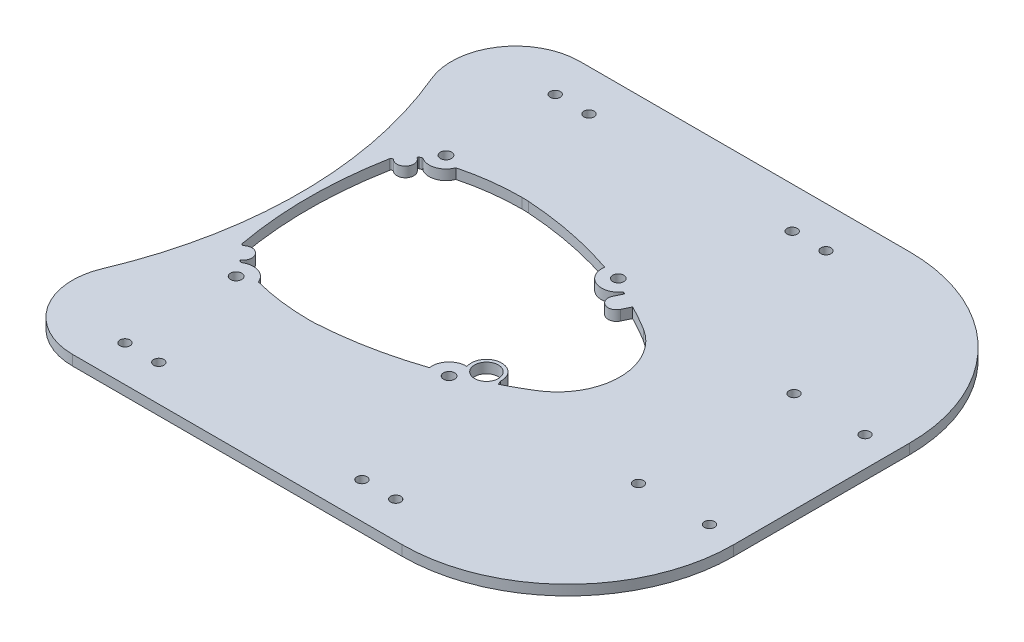
SolidWorks part; units mm, degrees
ref_plane "前视基准面" through (0, 0, 0) normal (0, 0, 1) x (1, 0, 0)
ref_plane "上视基准面" through (0, 0, 0) normal (0, 1, 0) x (1, 0, 0)
ref_plane "右视基准面" through (0, 0, 0) normal (1, 0, 0) x (0, 0, -1)
sketch "草图1" plane through (0, 0, 0) normal (0, 1, 0) x (1, 0, 0)
  line L1 (-102.5, -75) -> (102.5, -75)
  line L2 (-102.5, -75) -> (-102.5, 75)
  line L3 (-102.5, 75) -> (102.5, 75)
  line L4 (102.5, -75) -> (102.5, 75)
  line L5 (-102.5, -75) -> (102.5, 75) construction
  line L6 (-102.5, 75) -> (102.5, -75) construction
  point P0 (0, 0)
  dimension "D1" = 150
  dimension "D2" = 205
extrude "凸台-拉伸1" add sketch "草图1" along normal blind 3
fillet "圆角4" radius 49 4 edges at (102.5, 1.5, 75) (102.5, 1.5, -75) (-102.5, 1.5, -75) (-102.5, 1.5, 75)
sketch "草图7" plane through (0, 3, 0) normal (0, 1, 0) x (1, 0, 0)
  circle A4 centre (-29.1574, -64.3015) radius 1.5
  circle A5 centre (-39.1574, -64.3015) radius 1.5
  circle A6 centre (30.8947, -64.3015) radius 1.5
  circle A7 centre (40.8947, -64.3015) radius 1.5
extrude "切除-拉伸8" cut sketch "草图7" against normal blind 3
sketch "草图9" plane through (0, 3, 0) normal (0, 1, 0) x (1, 0, 0)
  circle A4 centre (-39.1574, 62.8977) radius 1.5
  circle A5 centre (-29.1574, 62.8977) radius 1.5
  circle A6 centre (30.8947, 62.8977) radius 1.5
  circle A7 centre (40.8947, 62.8977) radius 1.5
extrude "切除-拉伸10" cut sketch "草图9" against normal blind 10
sketch "草图10" plane through (0, 3, 0) normal (0, 1, 0) x (1, 0, 0)
  line L0 (-73.5433, 70.7131) -> (-101.7166, 64.6417)
  line L1 (-101.7166, 64.6417) -> (-120.7329, 20.0424)
  line L2 (-120.7329, 20.0424) -> (-122.2378, -19.2215)
  line L3 (-122.2378, -19.2215) -> (-120.7329, -55.0652)
  line L4 (-120.7329, -55.0652) -> (-105.1368, -72.987)
  line L5 (-105.1368, -72.987) -> (-73.5433, -70.7131)
  arc A0 (-73.5433, 70.7131) -> (-73.5433, -70.7131) centre (-176.7188, 0) cw
  arc A1 (-53.5, 75) -> (-102.5, 26) centre (-53.5, 26) ccw construction
  arc A2 (-102.5, -26) -> (-53.5, -75) centre (-53.5, -26) ccw construction
extrude "切除-拉伸11" cut sketch "草图10" against normal blind 10
fillet "圆角6" radius 19 2 edges at (-73.5433, 1.5, 70.7131) (-73.5433, 1.5, -70.7131)
sketch "草图12" plane through (0, 0, 0) normal (0, -1, 0) x (1, 0, 0)
  arc A8 (18.8978, 24.8951) -> (15.5979, 24.8762) centre (17.2479, 24.8856) ccw
  arc A9 (15.5979, 24.8762) -> (18.8978, 24.8951) centre (17.2479, 24.8856) ccw
  arc A10 (-38.1065, 30.8538) -> (-41.4064, 30.8349) centre (-39.7565, 30.8444) ccw
  arc A11 (-41.4064, 30.8349) -> (-38.1065, 30.8538) centre (-39.7565, 30.8444) ccw
  arc A12 (-38.0616, -31.1462) -> (-41.3616, -31.1651) centre (-39.7116, -31.1556) ccw
  arc A13 (-41.3616, -31.1651) -> (-38.0616, -31.1462) centre (-39.7116, -31.1556) ccw
  arc A14 (18.934, -25.1049) -> (15.6341, -25.1238) centre (17.284, -25.1144) ccw
  arc A15 (15.6341, -25.1238) -> (18.934, -25.1049) centre (17.284, -25.1144) ccw
extrude "切除-拉伸12" cut sketch "草图12" against normal blind 10
sketch "草图13" plane through (0, 0, 0) normal (0, -1, 0) x (1, 0, 0)
  line L4 (26.6148, 19.6122) -> (26.6662, 19.7183)
  line L5 (26.1598, 18.6664) -> (26.6148, 19.6122)
  line L6 (25.5325, -17.527) -> (26.6904, -19.9357)
  line L7 (22.1857, -22.1056) -> (21.0261, -19.6931)
  line L8 (12.4104, -25.9802) -> (12.3869, -25.836)
  line L9 (-47.1197, 21.6577) -> (-47.2203, 21.6765)
  arc A38 (-15.7291, -31.5759) -> (12.4104, -25.9802) centre (-22.6349, 76.7042) ccw
  arc A39 (-17.7112, -31.6397) -> (-15.7291, -31.5759) centre (-17.734, -0.1397) ccw
  arc A40 (-35.0726, -29.4288) -> (-17.7112, -31.6397) centre (-17.7611, 37.2403) ccw
  arc A41 (-35.0726, -29.4288) -> (-42.3545, -26.9702) centre (-39.7116, -31.1556) ccw
  arc A42 (-42.6229, -26.9963) -> (-42.3545, -26.9702) centre (-42.5147, -26.7166) ccw
  arc A43 (-43.249, -26.7505) -> (-42.6229, -26.9963) centre (-17.7611, 37.2403) ccw
  arc A44 (-43.3072, -26.224) -> (-43.249, -26.7505) centre (-43.138, -26.4718) ccw
  arc A45 (-43.3072, -26.224) -> (-42.2167, -24.1449) centre (-44.7167, -24.1593) ccw
  arc A46 (-42.2167, -24.1449) -> (-46.3672, -22.2816) centre (-44.7167, -24.1593) ccw
  arc A47 (-47.1887, -21.9985) -> (-46.3672, -22.2816) centre (-46.6973, -21.9061) ccw
  arc A48 (-49.2321, -0.7557) -> (-47.1887, -21.9985) centre (69.2659, -0.0768) ccw
  arc A49 (-47.2203, 21.6765) -> (-49.2321, -0.7557) centre (69.2659, -0.0768) ccw
  arc A50 (-44.3688, 21.2245) -> (-43.2648, 26.0273) centre (-44.7514, 23.8407) ccw
  arc A51 (-43.234, 26.3004) -> (-43.2648, 26.0273) centre (-43.1761, 26.1556) ccw
  arc A52 (-42.47, 26.5332) -> (-42.6096, 26.5466) centre (-42.5531, 26.4012) ccw
  arc A53 (-42.6096, 26.5466) -> (-43.234, 26.3004) centre (-17.707, -37.5197) ccw
  arc A54 (-42.47, 26.5332) -> (-35.0066, 29.0036) centre (-39.7565, 30.8444) ccw
  arc A55 (-17.7567, 31.2162) -> (-35.0066, 29.0036) centre (-17.707, -37.5197) ccw
  arc A56 (-15.7836, 31.1555) -> (-17.7567, 31.2162) centre (-17.734, -0.1397) ccw
  arc A57 (12.2111, 25.6472) -> (-15.7836, 31.1555) centre (-22.5237, -76.9906) ccw
  arc A58 (12.2111, 25.6472) -> (17.4425, 19.7953) centre (17.2479, 24.8856) ccw
  arc A59 (25.177, 18.2928) -> (22.4277, 21.6912) centre (21.677, 18.2727) ccw
  arc A60 (22.4277, 21.6912) -> (18.7403, 20.1768) centre (21.677, 18.2727) ccw
  arc A61 (18.7403, 20.1768) -> (18.1771, 18.2527) centre (21.677, 18.2727) ccw
  arc A62 (18.1771, 18.2527) -> (25.177, 18.2928) centre (21.677, 18.2727) ccw
  arc A63 (19.453, 14.3607) -> (19.4759, 14.3478) centre (21.677, 18.2727) ccw
  arc A64 (17.4425, 19.7953) -> (19.453, 14.3607) centre (21.677, 18.2727) ccw
  arc A65 (19.4759, 14.3478) -> (26.177, 18.2985) centre (21.677, 18.2727) ccw
  arc A66 (26.177, 18.2985) -> (26.1598, 18.6664) centre (21.677, 18.2727) ccw
  arc A67 (33.8838, 15.694) -> (26.6662, 19.7183) centre (-22.5237, -76.9906) ccw
  arc A68 (42.7656, -0.0033) -> (33.8838, 15.694) centre (24.2659, -0.1093) ccw
  arc A69 (33.9067, -15.8988) -> (42.7656, -0.0033) centre (24.2659, -0.1093) ccw
  arc A70 (26.6904, -19.9357) -> (33.9067, -15.8988) centre (-22.6349, 76.7042) ccw
  arc A71 (25.5325, -17.527) -> (20.7794, -18.6244) centre (23.2793, -18.61) ccw
  arc A72 (20.7794, -18.6244) -> (21.0261, -19.6931) centre (23.2793, -18.61) ccw
  arc A73 (22.0545, -22.165) -> (22.1857, -22.1056) centre (-22.6349, 76.7042) ccw
  arc A74 (21.4475, -22.4371) -> (22.0545, -22.165) centre (-22.6349, 76.7042) ccw
  arc A75 (21.4475, -22.4371) -> (12.3869, -25.836) centre (17.284, -25.1144) ccw
  spline S5 degree 3 poles (-46.4755, 21.8737) (-46.4814, 21.879) (-46.4937, 21.8893) (-46.5133, 21.9038) (-46.5339, 21.9171) (-46.5553, 21.9291) (-46.5779, 21.9399) (-46.6017, 21.9495) (-46.6272, 21.9578) (-46.6538, 21.9645) (-46.6805, 21.9693) (-46.7093, 21.9724) (-46.7384, 21.9733) (-46.7671, 21.972) (-46.7957, 21.9687) (-46.8243, 21.9632) (-46.853, 21.9554) (-46.8812, 21.9453) (-46.9081, 21.9334) (-46.9338, 21.9196) (-46.9584, 21.9039) (-46.982, 21.8863) (-47.0038, 21.8673) (-47.0245, 21.8464) (-47.0431, 21.8245) (-47.0597, 21.8018) (-47.0742, 21.7787) (-47.0867, 21.7555) (-47.0975, 21.7318) (-47.1066, 21.7076) (-47.1142, 21.6826) (-47.118, 21.666) (-47.1197, 21.6577) knots 0 0 0 0 0.033333 0.066667 0.1 0.133333 0.166667 0.2 0.233333 0.266667 0.3 0.333333 0.366667 0.4 0.433333 0.466667 0.5 0.533333 0.566667 0.6 0.633333 0.666667 0.7 0.733333 0.766667 0.8 0.833333 0.866667 0.9 0.933333 0.966667 1 1 1 1 weights 1 1 1 1 1 1 1 1 1 1 1 1 1 1 1 1 1 1 1 1 1 1 1 1 1 1 1 1 1 1 1 1 1
  spline S6 degree 3 poles (-46.4755, 21.8737) (-46.4415, 21.8443) (-46.3735, 21.7854) (-46.2671, 21.7046) (-46.1576, 21.6292) (-46.0447, 21.5596) (-45.9284, 21.4957) (-45.7752, 21.4209) (-45.5833, 21.3436) (-45.3519, 21.2729) (-45.198, 21.2441) (-45.1198, 21.2295) knots 0 0 0 0 0.081532 0.163516 0.24623 0.329946 0.414924 0.501414 0.663064 0.828812 1 1 1 1
  spline S7 degree 3 poles (-45.1198, 21.2295) (-45.1035, 21.2269) (-45.0702, 21.2219) (-45.0186, 21.2152) (-44.9662, 21.2095) (-44.9129, 21.205) (-44.8587, 21.2015) (-44.8032, 21.1992) (-44.7477, 21.1982) (-44.6921, 21.1984) (-44.6368, 21.1998) (-44.5822, 21.2025) (-44.5282, 21.2063) (-44.4745, 21.2112) (-44.4212, 21.2173) (-44.3862, 21.222) (-44.3688, 21.2245) knots 0 0 0 0 0.071429 0.142857 0.214286 0.285714 0.357143 0.428571 0.5 0.571429 0.642857 0.714286 0.785714 0.857143 0.928571 1 1 1 1 weights 1 1 1 1 1 1 1 1 1 1 1 1 1 1 1 1 1
extrude "切除-拉伸13" cut sketch "草图13" against normal blind 10
sketch "草图14" plane through (0, 3, 0) normal (0, 1, 0) x (1, 0, 0)
  circle A4 centre (93.75, -24.4036) radius 1.5
  circle A5 centre (93.75, 21.5964) radius 1.5
  circle A6 centre (72.75, 21.5964) radius 1.5
  circle A7 centre (72.75, -24.4036) radius 1.5
extrude "切除-拉伸14" cut sketch "草图14" against normal blind 10
